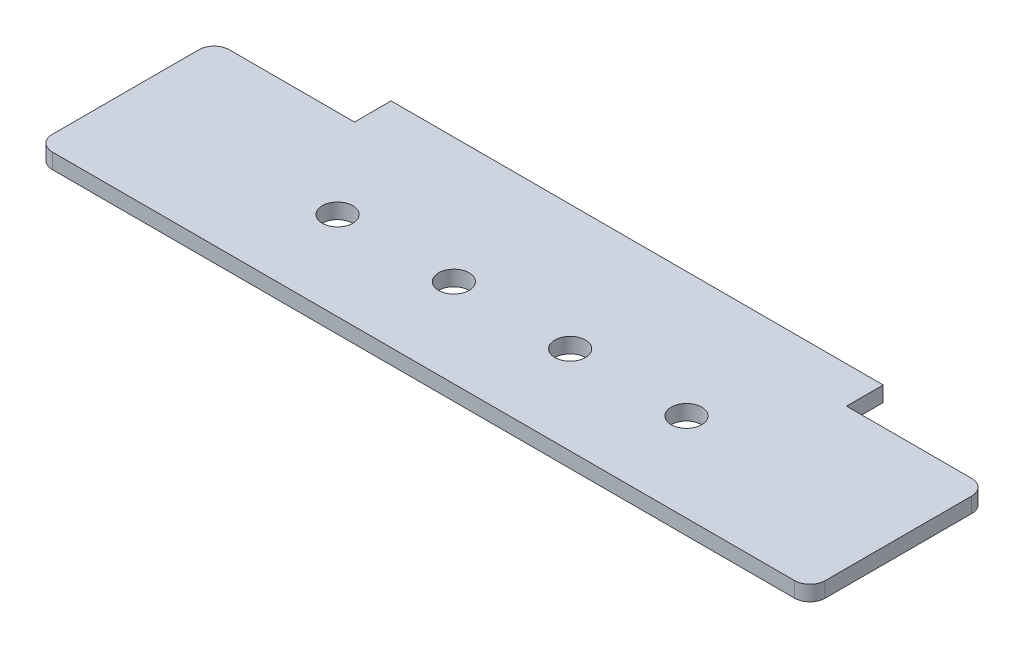
SolidWorks part; units mm, degrees
ref_plane "Front Plane" through (0, 0, 0) normal (0, 0, 1) x (1, 0, 0)
ref_plane "Top Plane" through (0, 0, 0) normal (0, 1, 0) x (1, 0, 0)
ref_plane "Right Plane" through (0, 0, 0) normal (1, 0, 0) x (0, 0, -1)
sketch "Sketch1" plane through (0, 0, 0) normal (0, 1, 0) x (1, 0, 0)
  line L0 (13.775, 2.9) -> (17.875, 2.9)
  line L1 (-6.445, 2.9) -> (-2.345, 2.9)
  line L2 (-6.945, 2.4) -> (-6.945, -2.4)
  line L3 (-6.445, -2.9) -> (17.875, -2.9)
  line L4 (18.375, 2.4) -> (18.375, -2.4)
  line L5 (-2.345, 4.1) -> (13.775, 4.1)
  line L6 (-2.345, 4.1) -> (-2.345, 2.9)
  line L8 (13.775, 4.1) -> (13.775, 2.9)
  line L9 (-6.945, 0) -> (18.375, 0) construction
  circle A0 centre (0, 0) radius 0.5
  circle A1 centre (3.81, 0) radius 0.5
  circle A2 centre (7.62, 0) radius 0.5
  circle A3 centre (11.43, 0) radius 0.5
  arc A4 (-6.445, 2.9) -> (-6.945, 2.4) centre (-6.445, 2.4) ccw
  arc A5 (17.875, 2.9) -> (18.375, 2.4) centre (17.875, 2.4) cw
  arc A6 (17.875, -2.9) -> (18.375, -2.4) centre (17.875, -2.4) ccw
  arc A7 (-6.945, -2.4) -> (-6.445, -2.9) centre (-6.445, -2.4) ccw
  point P18 (0, 0)
  point P19 (0, 0)
  point P20 (5.715, 0)
  point P22 (0, 0)
  point P25 (-6.945, 2.9)
  point P30 (18.375, -2.9)
  point P33 (-6.945, -2.9)
  dimension "D6" = 1
  dimension "D8" = 3.81
  dimension "D9" = 3.81
  dimension "D11" = 0.5
  dimension "D1" = 25.32
  dimension "D2" = 5.8
  dimension "D3" = 4.6
  dimension "D4" = 4.6
  dimension "D5" = 7
  dimension "D7" = 3.81
  dimension "D10" = 1.905
extrude "Boss-Extrude1" add sketch "Sketch1" along normal blind 0.5
